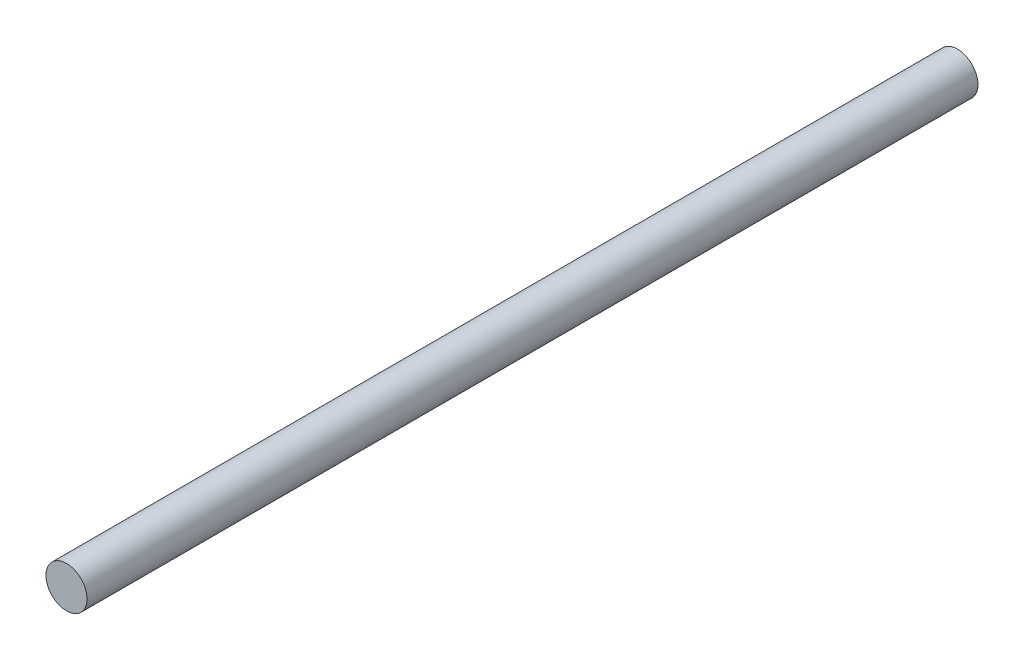
SolidWorks part; units mm, degrees
material "6061 合金"
ref_plane "前视基准面" through (0, 0, 0) normal (0, 0, 1) x (1, 0, 0)
ref_plane "上视基准面" through (0, 0, 0) normal (0, 1, 0) x (1, 0, 0)
ref_plane "右视基准面" through (0, 0, 0) normal (1, 0, 0) x (0, 0, -1)
sketch "草图1" plane through (0, 0, 0) normal (0, 0, 1) x (1, 0, 0)
  circle A0 centre (0, 0) radius 3
  dimension "D1" = 6
extrude "凸台-拉伸1" add sketch "草图1" along normal blind 130
cosmetic thread "装饰螺纹线2" parameters "D1"=16, "D2"=4.891
